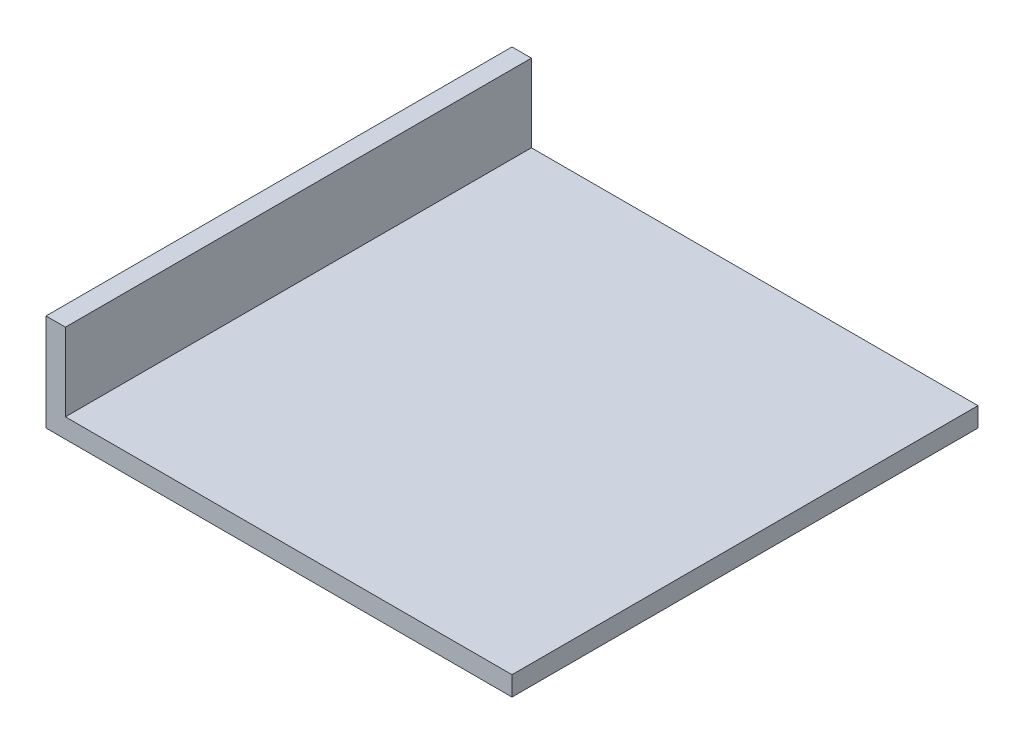
SolidWorks part; units mm, degrees
ref_plane "Front Plane" through (0, 0, 0) normal (0, 0, 1) x (1, 0, 0)
ref_plane "Top Plane" through (0, 0, 0) normal (0, 1, 0) x (1, 0, 0)
ref_plane "Right Plane" through (0, 0, 0) normal (1, 0, 0) x (0, 0, -1)
sketch "Sketch1" plane through (0, 0, 0) normal (0, 1, 0) x (1, 0, 0)
  line L1 (-304.8, -304.8) -> (304.8, -304.8)
  line L2 (-304.8, -304.8) -> (-304.8, 304.8)
  line L3 (-304.8, 304.8) -> (304.8, 304.8)
  line L4 (304.8, -304.8) -> (304.8, 304.8)
  line L5 (-304.8, -304.8) -> (304.8, 304.8) construction
  line L6 (-304.8, 304.8) -> (304.8, -304.8) construction
  point P0 (0, 0)
  dimension "D1" = 609.6
  dimension "D2" = 609.6
extrude "Boss-Extrude1" add sketch "Sketch1" along normal blind 25.4
sketch "Sketch2" plane through (0, 25.4, 0) normal (0, 1, 0) x (1, 0, 0)
  line L0 (-304.8, -304.8) -> (304.8, -304.8) construction
  line L1 (-304.8, 304.8) -> (-279.4, 304.8)
  line L2 (-304.8, 304.8) -> (-304.8, -304.8)
  line L3 (-304.8, -304.8) -> (-279.4, -304.8)
  line L4 (-279.4, 304.8) -> (-279.4, -304.8)
  dimension "D1" = 25.4
extrude "Boss-Extrude2" add sketch "Sketch2" along normal blind 101.6
